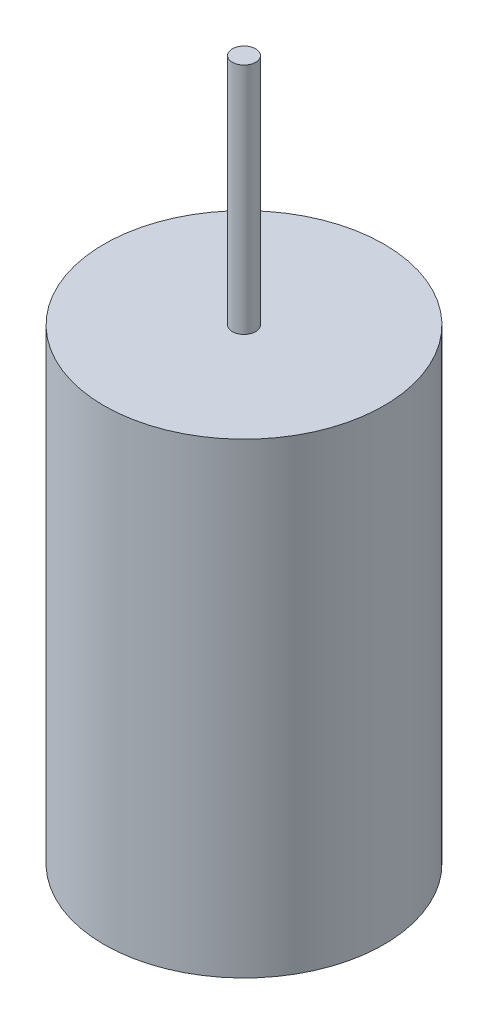
SolidWorks part; units mm, degrees
ref_plane "Front Plane" through (0, 0, 0) normal (0, 0, 1) x (1, 0, 0)
ref_plane "Top Plane" through (0, 0, 0) normal (0, 1, 0) x (1, 0, 0)
ref_plane "Right Plane" through (0, 0, 0) normal (1, 0, 0) x (0, 0, -1)
sketch "Sketch1" plane through (0, 0, 0) normal (0, 1, 0) x (1, 0, 0)
  circle A0 centre (0, 0) radius 3
  dimension "D1" = 6
extrude "Boss-Extrude1" add sketch "Sketch1" along normal blind 10
sketch "Sketch2" plane through (0, 10, 0) normal (0, 1, 0) x (1, 0, 0)
  circle A0 centre (0, 0) radius 0.25
  dimension "D1" = 0.5
extrude "Boss-Extrude2" add sketch "Sketch2" along normal blind 5
